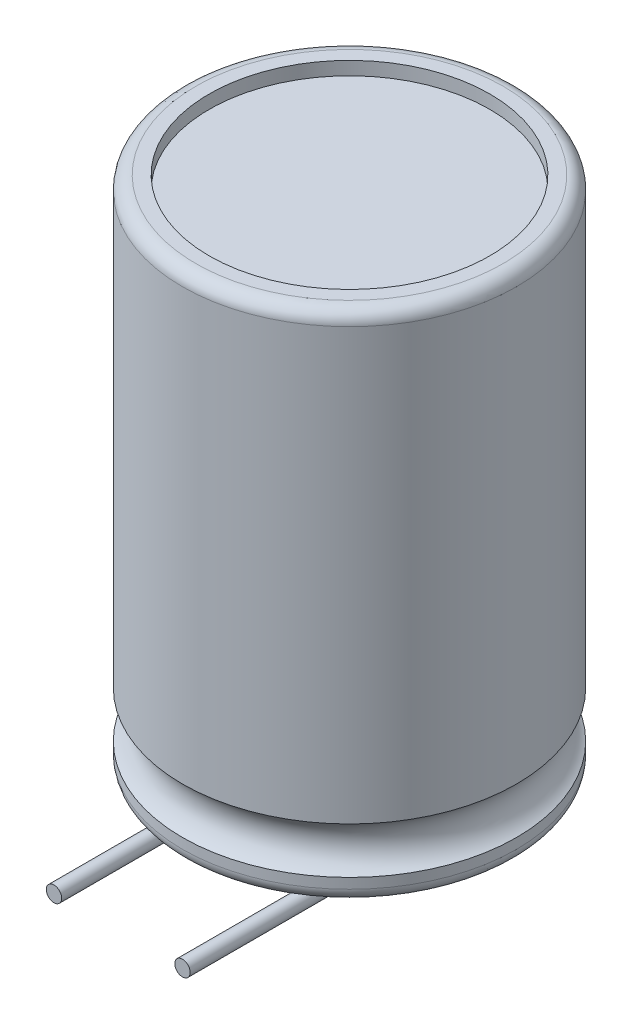
SolidWorks part; units mm, degrees
material "6061 Alloy"
ref_plane "Front" through (0, 0, 0) normal (0, 0, 1) x (1, 0, 0)
ref_plane "Top" through (0, 0, 0) normal (0, 1, 0) x (1, 0, 0)
ref_plane "Right" through (0, 0, 0) normal (1, 0, 0) x (0, 0, -1)
sketch "Sketch1" plane through (0, 0, 0) normal (0, 0, 1) x (1, 0, 0)
  line L0 (0, 0.52) -> (0, 19.48) construction
  line L1 (-2.8, 0) -> (-2.2, 0) construction
  line L2 (6.5, 2.7207) -> (6.5, 19.48)
  line L3 (5.46, 0) -> (5.98, 0)
  line L4 (0, 0.52) -> (0, 19.48)
  line L5 (5.46, 20) -> (5.98, 20)
  line L6 (6.5, 0.52) -> (6.5, 0.9193)
  line L7 (0, 0.52) -> (5.46, 0.52)
  line L8 (5.46, 0.52) -> (5.46, 0)
  line L9 (5.46, 20) -> (5.46, 19.48)
  line L10 (5.46, 19.48) -> (0, 19.48)
  line L11 (2.2, 0) -> (2.8, 0) construction
  line L12 (-2.5, 0) -> (0, 0) construction
  line L13 (0, 0) -> (2.5, 0) construction
  arc A0 (6.5, 0.9193) -> (6.5, 2.7207) centre (7.02, 1.82) cw
  arc A1 (5.98, 20) -> (6.5, 19.48) centre (5.98, 19.48) cw
  arc A2 (5.98, 0) -> (6.5, 0.52) centre (5.98, 0.52) ccw
  dimension "D3" = 1.04
  dimension "D9" = 0.52
  dimension "D1" = 13
  dimension "D2" = 20
  dimension "D4" = 1.82
  dimension "D5" = 14.04
  dimension "D6" = 1.04
  dimension "D7" = 0.52
  dimension "D8" = 0.52
  dimension "D10" = 0.6
  dimension "D11" = 5
revolve "Body" add sketch "Sketch1" angle 360 about L0
sketch "Sketch16" plane through (0, 0.52, 0) normal (0, 1, 0) x (1, 0, 0)
  line L0 (-2.8, 0) -> (-2.2, 0) construction
  line L1 (2.2, 0) -> (2.8, 0) construction
  line L2 (2.2, 0) -> (2.8, 0) construction
  line L3 (2.8, 0) -> (2.8, 0.3) construction
  line L4 (2.8, 0.3) -> (2.5, 0.3) construction
  circle A0 centre (-2.5, 0) radius 0.3
  circle A1 centre (2.5, 0) radius 0.3
sketch "Эскиз1" plane through (0, 0, 0) normal (1, 0, 0) x (0, 0, -1)
  line L0 (0, 0.52) -> (0, 0.02)
  line L1 (0.3, 0.52) -> (-0.3, 0.52) construction
  line L2 (-1, -0.98) -> (-9, -0.98)
  arc A0 (-1, -0.98) -> (0, 0.02) centre (-1, 0.02) ccw
  dimension "D1" = 1
  dimension "D2" = 1.5
  dimension "D3" = 9
sweep "По траектории1" add profiles "Sketch16" path "Эскиз1"
equation "\"D4@Sketch1\"=0.14*\"D1@Sketch1\""
equation "\"D3@Sketch1\"=1/12.5*\"D1@Sketch1\""
equation "\"D7@Sketch1\"=.5/12.5*\"D1@Sketch1\""
equation "\"D6@Sketch1\"=\"D3@Sketch1\""
equation "\"D8@Sketch1\"=\"D7@Sketch1\""
equation "\"D9@Sketch1\"=\"D7@Sketch1\""
equation "\"D5@Sketch1\"=13.5/12.5*\"D1@Sketch1\""
equation "\"D1@Sketch6\"=3/12.5*\"D2@Sketch6\""
